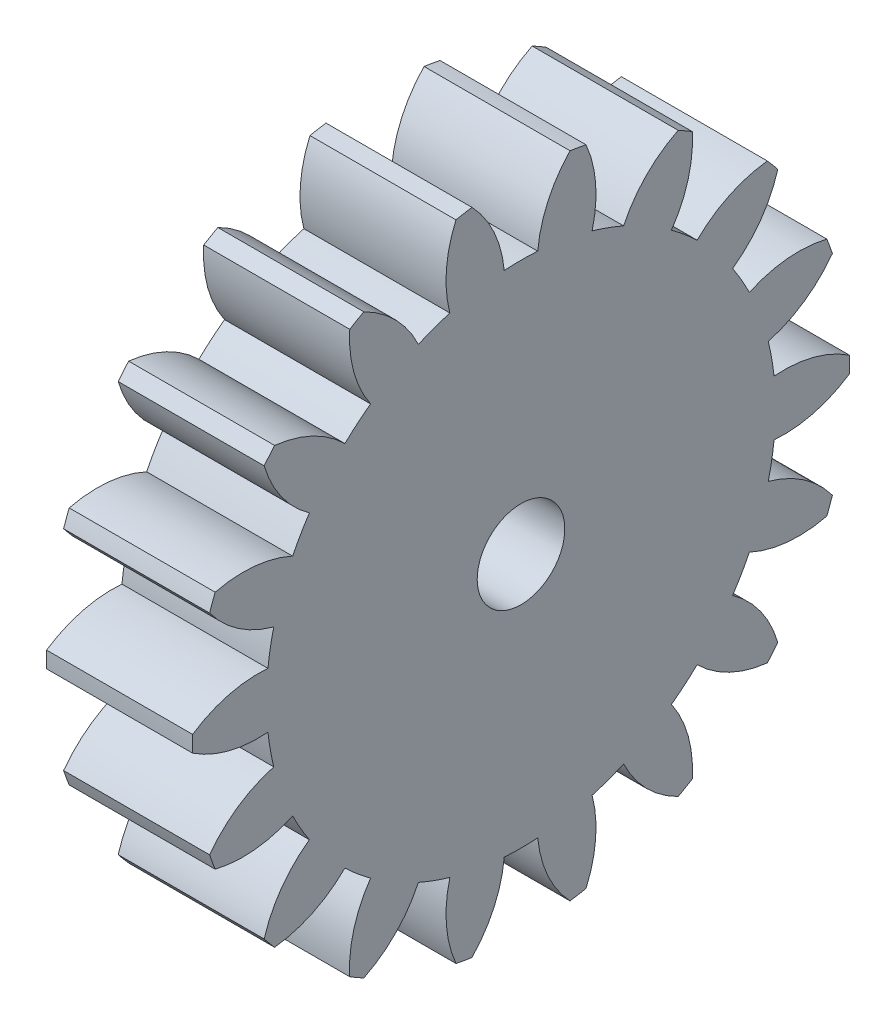
SolidWorks part; units mm, degrees
ref_plane "Plane1" through (0, 0, 0) normal (0, 0, 1) x (1, 0, 0)
ref_plane "Plane2" through (0, 0, 0) normal (0, 1, 0) x (1, 0, 0)
ref_plane "Plane3" through (0, 0, 0) normal (1, 0, 0) x (0, 0, -1)
sketch "HoldingSke" plane through (0, 0, 0) normal (0, 1, 0) x (1, 0, 0)
  line L0 (0, 0) -> (0.8454, -0.2747)
  line L1 (-15, 0) -> (100, 0) construction
  line L2 (0, 0) -> (-2.1039, 2.3779)
  line L3 (0, 0) -> (-11.863, 4.5341)
  line L4 (0, 0) -> (8.2133, 2.6687)
  line L5 (0, 0) -> (-46.8476, -17.4728)
  line L6 (0, 0) -> (-4.1448, -2.7965)
  line L7 (-2.1039, 2.3779) -> (8.6586, 51.2059)
  line L8 (-76.2, 54.61) -> (-75.7, 54.61)
  line L9 (-71.009, 38.7566) -> (-53.1078, 45.2721)
  line L10 (-76.2, 71.12) -> (104.1128, 71.12)
  line L11 (0, 0) -> (-5, 0)
  line L12 (-76.2, 101.6) -> (-76.158, 101.6)
  line L13 (24.9733, 27.94) -> (52.9518, 28.4284)
  line L14 (24.9733, 27.94) -> (24.9743, 27.94)
  line L15 (24.9733, 27.94) -> (100.4006, 29.5858)
  line L16 (-63.627, -1.125) -> (-12.827, -1.125)
  circle A0 centre (0, 0) radius 1.5
  circle A1 centre (0, 0) radius 8.7177
  circle A2 centre (0, 0) radius 37.5
  circle A3 centre (0, 0) radius 1.5
  dimension "MHD" = 17.4355
  dimension "Hub_dia" = 75
  dimension "Bore" = 3
  dimension "MBD" = 3
  dimension "Num_teeth" = 18
  dimension "Pitch" = 0.8889
  dimension "Overall_len" = 50
  dimension "Show_teeth" = 18
  dimension "Thickness" = 5
  dimension "OAL" = 50.0001
  dimension "T_dim" = 0.5
  dimension "Ap" = 20
  dimension "H" = 19.05
  dimension "Pitch_radius" = 180.3128
  dimension "Width" = 5
  dimension "Backlash" = 0.042
  dimension "Addendum_fac" = 1
  dimension "Dedendum_fac" = 1.25
  dimension "Clearance_fac" = 0.25
  dimension "Dedendum_add" = 0.001
  dimension "Module" = 1.125
sketch "BasProSke" plane through (0, 0, 0) normal (0, 1, 0) x (1, 0, 0)
  line L0 (-10, 0) -> (60, 0) construction
  line L1 (0, 0) -> (0, 11.25)
  line L2 (0, 0) -> (5, 0)
  line L3 (5, 0) -> (5, 11.25)
  line L4 (5, 11.25) -> (0, 11.25)
  dimension "Thickness" = 5
  dimension "Diameter" = 22.5
revolve "Base-Revolve" add sketch "BasProSke" angle 360 about L0
sketch "TooCutSke" plane through (0, 0, 0) normal (1, 0, 0) x (0, 0, -1)
  line L1 (0, 0) -> (0, 107) construction
  line L2 (0, 0) -> (-0.9559, 10.0798) construction
  line L3 (0, 0) -> (-3.5051, 19.8786) construction
  line L4 (-0.9559, 10.0798) -> (-1.7526, 9.9393) construction
  arc A0 (0.5734, 8.6989) -> (-0.5734, 8.6989) centre (0, 0) ccw
  arc A1 (1.7004, 11.1464) -> (-1.7004, 11.1464) centre (0, 0) ccw
  circle A2 centre (0, 0) radius 10.125 construction
  circle A3 centre (0, 0) radius 9.5144 construction
  arc A4 (-0.5734, 8.6989) -> (-1.7004, 11.1464) centre (-4.6061, 8.3251) ccw
  arc A5 (1.7004, 11.1464) -> (0.5734, 8.6989) centre (4.6061, 8.3251) ccw
  dimension "Root_dia" = 17.4355
  dimension "Overcut_dia" = 22.5508
  dimension "Pitch_dia" = 20.25
  dimension "Base_dia" = 19.0288
  dimension "Flank_rad" = 4.05
  dimension "Half_ang" = 10
  dimension "Half_CT" = 0.809
extrude "ToothCut" cut sketch "TooCutSke" along normal through all
fillet "Breaks" [suppressed] radius 0.0225
fillet "RootFillets" [suppressed] radius 0.2823
pattern_circular "TeethCuts" count 18 every 20 about axis through (-10, 0, 0) along (1, 0, 0) of "ToothCut", "RootFillets", "Breaks"
sketch "HubNeaOneSke" plane through (0, 0, 0) normal (-1, 0, 0) x (0, 0, 1)
  circle A0 centre (0, 0) radius 8.7177
  dimension "Diameter" = 17.4355
extrude "HubNearOne" [suppressed] add sketch "HubNeaOneSke" along normal blind 45.0001
sketch "HubNeaBotSke" plane through (0, 0, 0) normal (-1, 0, 0) x (0, 0, 1)
  circle A0 centre (0, 0) radius 8.7177
  dimension "Diameter" = 17.4355
extrude "HubNearBoth" [suppressed] add sketch "HubNeaBotSke" along normal blind 22.5
ref_plane "FarPln" through (5, 0, 0) normal (1, 0, 0) x (0, 0, -1)
sketch "HubFarSke" plane through (5, 0, 0) normal (1, 0, 0) x (0, 0, -1)
  circle A0 centre (0, 0) radius 8.7177
  dimension "Diameter" = 17.4355
extrude "HubFar" [suppressed] add sketch "HubFarSke" along normal blind 22.5
sketch "BorSke" plane through (0, 0, 0) normal (1, 0, 0) x (0, 0, -1)
  circle A0 centre (0, 0) radius 1.5
  dimension "Diameter" = 3
extrude "Bore" cut sketch "BorSke" along normal mid plane 100.0001
sketch "KeySke" plane through (0, 0, 0) normal (1, 0, 0) x (0, 0, -1)
  line L0 (-0.6, 0) -> (-0.6, 2)
  line L1 (-0.6, 2) -> (0.6, 2)
  line L2 (0.6, 2) -> (0.6, 0)
  line L3 (0, 0) -> (0, 34) construction
  line L4 (-0.6, 0) -> (0.6, 0)
  dimension "Offset" = 2
  dimension "Width" = 1.2
extrude "Keyway" [suppressed] cut sketch "KeySke" along normal mid plane 100.0001
pattern_circular "Keyway2" [suppressed] count 2 every 90 about axis through (-10, 0, 0) along (1, 0, 0)
equation "' \"Module@HoldingSke\" = 6.35"
equation "' \"Num_teeth@HoldingSke\" = 12"
equation "' \"Ap@HoldingSke\" =  20"
equation "' \"Ap@HoldingSke\" = 20"
equation "' \"Width@HoldingSke\" = 0.5 * 25.4"
equation "' \"Hub_dia@HoldingSke\"= 1 * 25.4"
equation "' \"Hub_dia@HoldingSke\" = 1 * 25.4"
equation "' \"Overall_len@HoldingSke\" = 1.0 * 25.4"
equation "' \"Bore@HoldingSke\" = 0.75 * 25.4"
equation "' \"T_dim@HoldingSke\" = 0.1 * 25.4"
equation "' \"Width@KeySke\" = 0.25 * 25.4"
equation "' \"Show_teeth@HoldingSke\" = 13"
equation "' \"Backlash@HoldingSke\" = 0.009 * 25.4"
equation "' \"Addendum_fac@HoldingSke\" = 1.0"
equation "' \"Dedendum_fac@HoldingSke\" = 1.25"
equation "' \"Dedendum_add@HoldingSke\" = 0.00005 * 25.4"
equation "' \"Clearance_fac@HoldingSke\" = 0.25"
equation "\"Pitch@HoldingSke\" = 1 / \"Module@HoldingSke\""
equation "\"Overcut_dia@TooCutSke\" = (\"Num_teeth@HoldingSke\" + 2 * \"Addendum_fac@HoldingSke\") / \"Pitch@HoldingSke\" + 0.002 * 25.4"
equation "\"Pitch_dia@TooCutSke\" = \"Num_teeth@HoldingSke\" / \"Pitch@HoldingSke\""
equation "\"Base_dia@TooCutSke\" = \"Num_teeth@HoldingSke\" / \"Pitch@HoldingSke\" * cos((\"Ap@HoldingSke\"  * 3.14159265 / 180))"
equation "\"Root_dia@TooCutSke\" = (\"Num_teeth@HoldingSke\" + 2) / \"Pitch@HoldingSke\" - 2 * (\"Addendum_fac@HoldingSke\" + \"Dedendum_fac@HoldingSke\") / \"Pitch@HoldingSke\" - \"Dedendum_add@HoldingSke\" * 2"
equation "\"Half_ang@TooCutSke\" = 180 / \"Num_teeth@HoldingSke\""
equation "\"Half_CT@TooCutSke\" = \"Num_teeth@HoldingSke\" / \"Pitch@HoldingSke\" * sin((3.14159265 / 2 / \"Num_teeth@HoldingSke\")) / 2 - 7 * \"Backlash@HoldingSke\" / 4"
equation "\"Flank_rad@TooCutSke\" = \"Num_teeth@HoldingSke\" / \"Pitch@HoldingSke\" / 5"
equation "\"Radius@RootFillets\" = \"Clearance_fac@HoldingSke\" / \"Pitch@HoldingSke\" + \"Dedendum_add@HoldingSke\""
equation "\"Break_rad@Breaks\" = 0.02 / \"Pitch@HoldingSke\""
equation "\"Thickness@HoldingSke\" = \"Width@HoldingSke\""
equation "\"OAL@HoldingSke\" = \"Thickness@HoldingSke\""
equation "\"MHD@HoldingSke\" = (\"Num_teeth@HoldingSke\" + 2) / \"Pitch@HoldingSke\" - 2 * (\"Addendum_fac@HoldingSke\" + \"Dedendum_fac@HoldingSke\")  / \"Pitch@HoldingSke\" - \"Dedendum_add@HoldingSke\" * 2"
equation "\"MBD@HoldingSke\" = (\"Num_teeth@HoldingSke\" + 2) / \"Pitch@HoldingSke\" - 2 * (\"Addendum_fac@HoldingSke\" + \"Dedendum_fac@HoldingSke\")  / \"Pitch@HoldingSke\" - \"Dedendum_add@HoldingSke\" * 2 - 0.002 * 25.4"
equation "\"MHD@HoldingSke\" = ((sgn( \"MHD@HoldingSke\" - \"Hub_dia@HoldingSke\" )-1)*( \"MHD@HoldingSke\" - \"Hub_dia@HoldingSke\" ))/-2+ \"Hub_dia@HoldingSke\""
equation "\"MBD@HoldingSke\" = ((sgn( \"MBD@HoldingSke\" - \"Bore@HoldingSke\" )-1)*( \"MBD@HoldingSke\" - \"Bore@HoldingSke\" ))/-2+ \"Bore@HoldingSke\""
equation "\"OAL@HoldingSke\" = ((sgn( \"OAL@HoldingSke\" - \"Overall_len@HoldingSke\" )+1)*( \"OAL@HoldingSke\" - \"Overall_len@HoldingSke\" ))/2 + \"Overall_len@HoldingSke\" + 0.000002 * 25.4"
equation "\"Num_teeth@TeethCuts\" = int( \"Show_teeth@HoldingSke\" ) + 1"
equation "\"Num_teeth@TeethCuts\" = ((sgn( \"Num_teeth@TeethCuts\" - \"Num_teeth@HoldingSke\" )-1)*( \"Num_teeth@TeethCuts\" - \"Num_teeth@HoldingSke\" ))/-2+ \"Num_teeth@HoldingSke\""
equation "\"Num_teeth@TeethCuts\" = ((sgn( \"Num_teeth@TeethCuts\" - 2.0)+1)*( \"Num_teeth@TeethCuts\" - 2.0))/2 +2.0"
equation "\"Angle@TeethCuts\" = 360.0 / \"Num_teeth@HoldingSke\""
equation "\"Diameter@BasProSke\" = (\"Num_teeth@HoldingSke\" + 2 * \"Addendum_fac@HoldingSke\") / \"Pitch@HoldingSke\""
equation "\"Thickness@BasProSke\"  = \"Thickness@HoldingSke\""
equation "' \"Fillet_rad@BasProSke\" =  \"Thickness@HoldingSke\" * 0.05"
equation "' \"Fillet_rad@BasProSke\" = \"Thickness@HoldingSke\" * 0.05"
equation "\"MHD@HoldingSke\" = ((sgn( \"MHD@HoldingSke\" - \"Root_dia@TooCutSke\" )-1)*( \"MHD@HoldingSke\" - \"Root_dia@TooCutSke\" ))/-2+ \"Root_dia@TooCutSke\""
equation "\"Diameter@HubNeaOneSke\" = \"MHD@HoldingSke\""
equation "\"Length@HubNearOne\" = \"OAL@HoldingSke\" - \"Thickness@BasProSke\""
equation "\"Diameter@HubNeaBotSke\" = \"MHD@HoldingSke\""
equation "\"Length@HubNearBoth\" = ( \"OAL@HoldingSke\" - \"Thickness@BasProSke\" ) / 2.0"
equation "\"Thickness@FarPln\" = \"Thickness@BasProSke\""
equation "\"Diameter@HubFarSke\" = \"MHD@HoldingSke\""
equation "\"Length@HubFar\" = ( \"OAL@HoldingSke\" - \"Thickness@BasProSke\" ) / 2.0"
equation "\"Diameter@BorSke\" = \"MBD@HoldingSke\""
equation "\"D1@Bore\" = \"OAL@HoldingSke\" * 2.0"
equation "\"D1@Keyway\" = \"OAL@HoldingSke\" * 2.0"
equation "\"Offset@KeySke\" = \"T_dim@HoldingSke\" + \"MBD@HoldingSke\" / 2.0"
